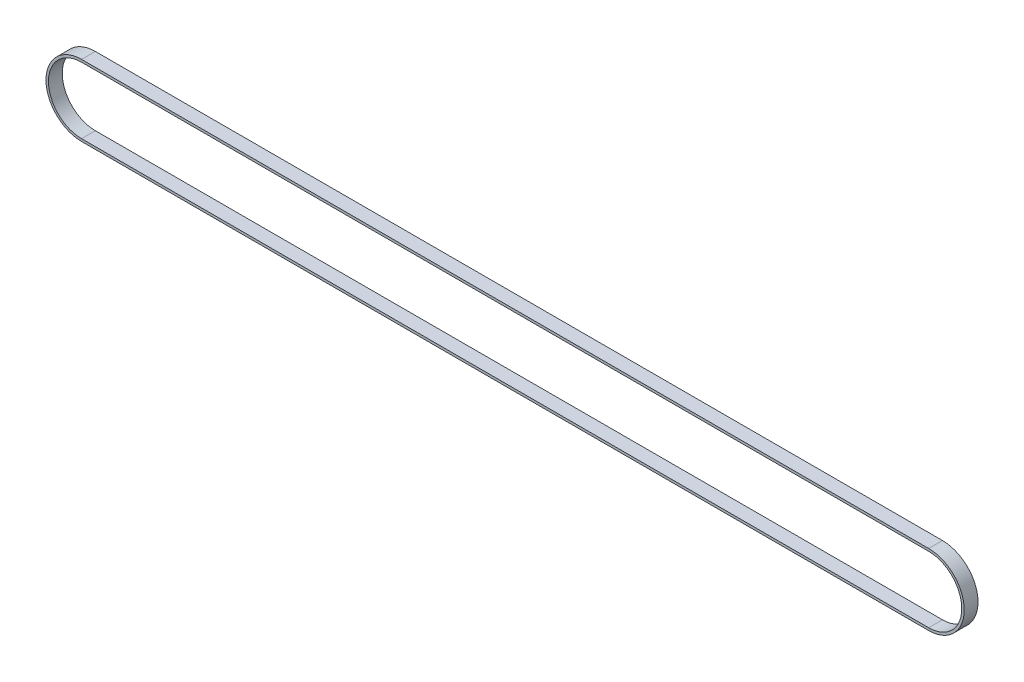
SolidWorks part; units mm, degrees
material "SKD11淬火HRC56-60"
ref_plane "前基準面" through (0, 0, 0) normal (0, 0, 1) x (1, 0, 0)
ref_plane "上基準面" through (0, 0, 0) normal (0, 1, 0) x (1, 0, 0)
ref_plane "右基準面" through (0, 0, 0) normal (1, 0, 0) x (0, 0, -1)
sketch "草图1" plane through (0, 0, 0) normal (0, 0, 1) x (1, 0, 0)
  line L0 (0, 0) -> (780, 0) construction
  line L1 (0, 30.47) -> (780, 30.47)
  line L2 (0, -30.47) -> (780, -30.47)
  line L3 (0, 32.74) -> (780, 32.74)
  line L4 (0, -32.74) -> (780, -32.74)
  arc A0 (0, 30.47) -> (0, -30.47) centre (0, 0) ccw
  arc A1 (780, -30.47) -> (780, 30.47) centre (780, 0) ccw
  arc A2 (780, -32.74) -> (780, 32.74) centre (780, 0) ccw
  arc A3 (0, 32.74) -> (0, -32.74) centre (0, 0) ccw
  point P3 (390, 0)
  dimension "D2" = 30.47
  dimension "D1" = 780
  dimension "D3" = 2.27
extrude "凸台-拉伸1" add sketch "草图1" along normal blind 12.7
